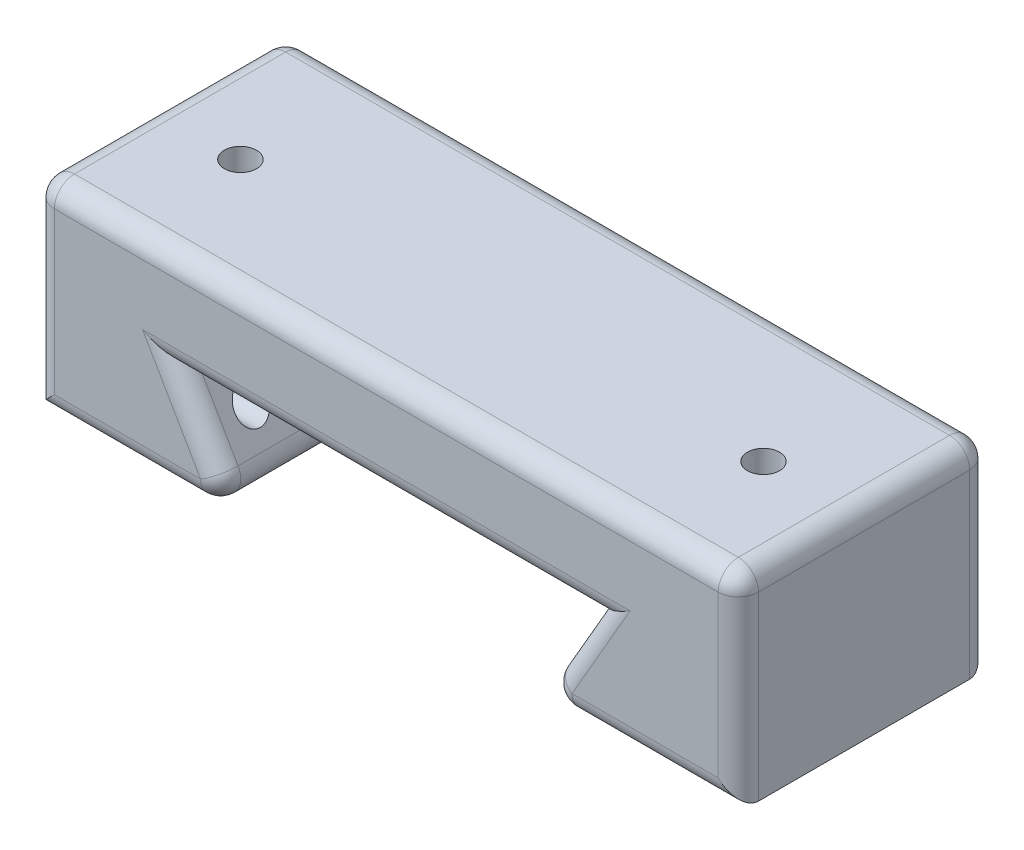
SolidWorks part; units mm, degrees
ref_plane "Front Plane" through (0, 0, 0) normal (0, 0, 1) x (1, 0, 0)
ref_plane "Top Plane" through (0, 0, 0) normal (0, 1, 0) x (1, 0, 0)
ref_plane "Right Plane" through (0, 0, 0) normal (1, 0, 0) x (0, 0, -1)
sketch "Sketch1" plane through (0, 0, 0) normal (0, 1, 0) x (1, 0, 0)
  line L0 (0, 0) -> (-26, 0) construction
  line L5 (0, 0) -> (26, 0) construction
  line L6 (-26, 0) -> (-26, -1) construction
  line L7 (-35, 12.5) -> (35, 12.5)
  line L8 (-35, 12.5) -> (-35, -12.5)
  line L9 (-35, -12.5) -> (35, -12.5)
  line L10 (35, 12.5) -> (35, -12.5)
  line L11 (-35, 12.5) -> (35, -12.5) construction
  line L12 (-35, -12.5) -> (35, 12.5) construction
  line L13 (26, 0) -> (26, -1) construction
  circle A7 centre (-26, -1) radius 1.6
  circle A8 centre (26, -1) radius 1.6
  dimension "D1" = 26
  dimension "D4" = 1
  dimension "D5" = 3.2
  dimension "D2" = 70
  dimension "D3" = 25
extrude "Boss-Extrude1" add sketch "Sketch1" along normal blind 10 contours A8 | A7
sketch "Sketch2" plane through (0, 0, 12.5) normal (0, 0, 1) x (1, 0, 0)
  line L0 (0, 0) -> (-35, 0) construction
  line L1 (-35, 0) -> (35, 0) construction
  line L2 (0, 0) -> (35, 0) construction
  line L4 (-35, 0) -> (-20.7735, 0)
  line L5 (-35, 0) -> (-35, -10)
  line L6 (-35, -10) -> (-15, -10)
  line L7 (35, 0) -> (35, -10)
  line L8 (15, -10) -> (20.7735, 0)
  line L10 (0, -14.85) -> (0, 14.85) construction
  line L11 (-15, -10) -> (-20.7735, 0)
  line L12 (15, -10) -> (35, -10)
  line L13 (20.7735, 0) -> (35, 0)
  dimension "D1" = 70
  dimension "D2" = 10
  dimension "D3" = 60
  dimension "D4" = 30
extrude "Boss-Extrude2" add sketch "Sketch2" against normal blind 25
sketch "Sketch3" plane through (0, 0, 0) normal (0, -1, 0) x (1, 0, 0)
  circle A0 centre (-26, 1) radius 3
  circle A1 centre (26, 1) radius 3
  dimension "D1" = 6
extrude "Cut-Extrude1" cut sketch "Sketch3" along normal through all
fillet "Fillet1" radius 2 20 edges at (15, -10, 0) (-15, -10, 0) (17.8868, -5, 12.5) (17.8868, -5, -12.5) (25, -10, 12.5) (25, -10, -12.5) (-25, -10, 12.5) (-25, -10, -12.5) (-17.8868, -5, 12.5) (-17.8868, -5, -12.5) (0, 0, -12.5) (0, 10, 12.5) (0, 0, 12.5) (0, 10, -12.5) (-35, 0, 12.5) (35, 0, 12.5) (35, 0, -12.5) (-35, 0, -12.5) (35, 10, 0) (-35, 10, 0)
sketch "Sketch4" plane through (0, 0, 12.5) normal (0, 0, 1) x (1, 0, 0)
  line L24 (-25.9697, 3) -> (25.9697, 3)
  line L26 (-25.9697, 3) -> (25.9697, 3)
  line L28 (25.9697, 3) -> (20.1962, -7)
  line L30 (25.9697, 3) -> (20.1962, -7)
  line L40 (20.1962, -7) -> (32, -7)
  line L42 (20.1962, -7) -> (32, -7)
  line L44 (32, -7) -> (32, 7)
  line L46 (32, -7) -> (32, 7)
  line L48 (32, 7) -> (-32, 7)
  line L49 (32, 7) -> (-32, 7)
  line L50 (-32, 7) -> (-32, -7)
  line L51 (-32, 7) -> (-32, -7)
  line L52 (-32, -7) -> (-20.1962, -7)
  line L53 (-32, -7) -> (-20.1962, -7)
  line L54 (-20.1962, -7) -> (-25.9697, 3)
  line L55 (-20.1962, -7) -> (-25.9697, 3)
  arc A0 (31, -5) -> (30, -6) centre (30, -5) cw
  arc A1 (22.7942, -4.5) -> (23.6603, -6) centre (23.6603, -5) ccw
  arc A2 (31, 5) -> (30, 6) centre (30, 5) ccw
  arc A3 (-23.6603, -6) -> (-22.7942, -4.5) centre (-23.6603, -5) ccw
  arc A4 (-31, -5) -> (-30, -6) centre (-30, -5) ccw
  arc A5 (-25.9697, 4) -> (-26.8357, 2.5) centre (-25.9697, 3) ccw
  arc A6 (-30, 6) -> (-31, 5) centre (-30, 5) ccw
  arc A7 (25.9697, 4) -> (26.8357, 2.5) centre (25.9697, 3) cw
  dimension "D2" = 1
  dimension "D3" = 1
  dimension "D1" = 1
extrude "Cut-Extrude2" [suppressed] cut sketch "Sketch4" against normal blind 2
ref_plane "Plane1" through (0, 0, 0) normal (0, 0, 1) x (1, 0, 0)
mirror "Mirror1" [suppressed] about plane through (0, 0, 0) normal (0, 0, 1)
sketch "Sketch6" plane through (-35, 0, 0) normal (-1, 0, 0) x (0, 0, 1)
  line L0 (-8.5, 10) -> (-8.5, -10) construction
  line L1 (-12.5, 10) -> (12.5, 10) construction
  line L2 (-10.5, -10) -> (10.5, -10) construction
  line L3 (-12.5, 10) -> (-12.5, -10) construction
  line L4 (-8.5, -4) -> (7.5, -4) construction
  circle A0 centre (-8.5, -4) radius 1.6
  circle A1 centre (7.5, -4) radius 1.6
  dimension "D1" = 3.2
  dimension "D2" = 4
  dimension "D3" = 6
  dimension "D4" = 16
extrude "Cut-Extrude3" cut sketch "Sketch6" against normal blind 27
sketch "Sketch7" plane through (0, -10, 0) normal (0, -1, 0) x (1, 0, 0)
  line L0 (-35, 9.1) -> (-35, 5.9) construction
  line L1 (-35, -6.9) -> (-35, -10.1) construction
  line L2 (-35, 9.1) -> (-35, 5.9) construction
  line L3 (-35, -6.9) -> (-35, -10.1) construction
  line L4 (-35, -8.5) -> (-30, -8.5) construction
  line L5 (-31.3, -11.5) -> (-28.7, -11.5)
  line L6 (-31.3, -11.5) -> (-31.3, -5.5)
  line L7 (-31.3, -5.5) -> (-28.7, -5.5)
  line L8 (-28.7, -11.5) -> (-28.7, -5.5)
  line L9 (-31.3, -11.5) -> (-28.7, -5.5) construction
  line L10 (-31.3, -5.5) -> (-28.7, -11.5) construction
  line L11 (-28.7, 4.5) -> (-31.3, 4.5)
  line L12 (-28.7, 4.5) -> (-28.7, 10.5)
  line L13 (-28.7, 10.5) -> (-31.3, 10.5)
  line L14 (-31.3, 4.5) -> (-31.3, 10.5)
  line L15 (-28.7, 4.5) -> (-31.3, 10.5) construction
  line L16 (-28.7, 10.5) -> (-31.3, 4.5) construction
  line L17 (-35, 7.5) -> (-30, 7.5) construction
  point P4 (-30, -8.5)
  point P9 (-30, 7.5)
  dimension "D1" = 2.6
  dimension "D2" = 6
  dimension "D3" = 5
extrude "Cut-Extrude4" cut sketch "Sketch7" against normal blind 11.25
